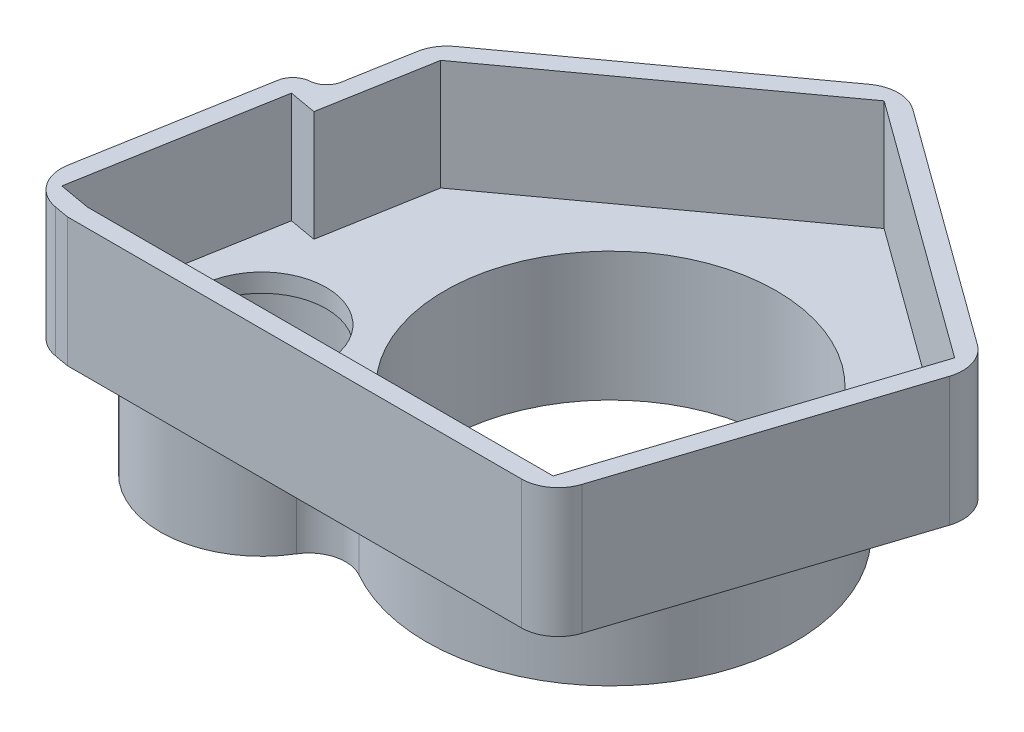
SolidWorks part; units mm, degrees
ref_plane "Front Plane" through (0, 0, 0) normal (0, 0, 1) x (1, 0, 0)
ref_plane "Top Plane" through (0, 0, 0) normal (0, 1, 0) x (1, 0, 0)
ref_plane "Right Plane" through (0, 0, 0) normal (1, 0, 0) x (0, 0, -1)
sketch "Sketch1" plane through (0, 0, 0) normal (0, 1, 0) x (1, 0, 0)
  line L0 (0, -73) -> (68.7664, -23.0383) construction
  line L1 (-68.7664, -23.0383) -> (0, -73) construction
  line L2 (68.7664, -23.0383) -> (42.5, 57.8016) construction
  line L3 (42.5, 57.8016) -> (-83.0207, 57.8016) construction
  line L4 (-83.0207, 57.8016) -> (-90.4067, 56.4992) construction
  line L5 (-90.4067, 56.4992) -> (-81.4141, 5.4992) construction
  line L6 (-81.4141, 5.4992) -> (-74.028, 6.8016) construction
  line L7 (-74.028, 6.8016) -> (-68.7664, -23.0383) construction
  line L8 (46.8593, 63.8016) -> (-83.5456, 63.8016)
  line L9 (-83.5456, 63.8016) -> (-97.3575, 61.3661) construction
  line L10 (-97.3575, 61.3661) -> (-86.281, -1.4515) construction
  line L11 (-86.281, -1.4515) -> (-78.895, -0.1492) construction
  line L12 (-78.895, -0.1492) -> (-74.2543, -26.4675) construction
  line L13 (-74.2543, -26.4675) -> (0, -80.4164) construction
  line L14 (0, -80.4164) -> (75.8199, -25.33) construction
  line L15 (75.8199, -25.33) -> (46.8593, 63.8016) construction
  line L16 (-74.028, 120.8016) -> (-68.7664, 150.6414) construction
  line L17 (-81.4141, 122.1039) -> (-74.028, 120.8016) construction
  line L18 (-90.4067, 71.1039) -> (-81.4141, 122.1039) construction
  line L19 (-83.0207, 69.8016) -> (-90.4067, 71.1039) construction
  line L20 (42.5, 69.8016) -> (-83.0207, 69.8016) construction
  line L21 (68.7664, 150.6414) -> (42.5, 69.8016) construction
  line L22 (-68.7664, 150.6414) -> (0, 200.6031) construction
  line L23 (0, 200.6031) -> (68.7664, 150.6414) construction
  line L24 (75.8199, 152.9332) -> (46.8593, 63.8016)
  line L25 (0, 208.0195) -> (75.8199, 152.9332)
  line L26 (-74.2543, 154.0706) -> (0, 208.0195)
  line L27 (-78.895, 127.7523) -> (-74.2543, 154.0706)
  line L28 (-86.281, 129.0546) -> (-78.895, 127.7523)
  line L29 (-97.3575, 66.237) -> (-86.281, 129.0546)
  line L30 (-83.5456, 63.8016) -> (-97.3575, 66.237)
  circle A0 centre (0, 0) radius 45 construction
  circle A1 centre (0, 127.6031) radius 45
  point P10 (-74.028, 6.8016)
  point P12 (0, 0)
  point P13 (-68.7664, -23.0383)
  point P14 (-68.7664, -23.0383)
  dimension "D16" = 90
  dimension "D1" = 85
  dimension "D2" = 85
  dimension "D3" = 125.5207
  dimension "D4" = 7.5
  dimension "D5" = 51
  dimension "D6" = 30.3001
  dimension "D7" = 85
  dimension "D8" = 57.8016
  dimension "D9" = 7.5
  dimension "D10" = 73
  dimension "D11" = 0
  dimension "D12" = 58.2816
  dimension "D13" = 90.4067
  dimension "D14" = 79.2223
  dimension "D15" = 74.028
  dimension "D17" = 72.523
  dimension "D18" = 137.5329
  dimension "D19" = 6
extrude "Boss-Extrude1" add sketch "Sketch1" along normal blind 35
sketch "Sketch2" plane through (0, 35, 0) normal (0, 1, 0) x (1, 0, 0)
  line L40 (69.942, 151.0233) -> (0, 201.8392)
  line L41 (43.2265, 68.8016) -> (69.942, 151.0233)
  line L42 (0, 201.8392) -> (-69.6811, 151.2129)
  line L43 (-69.6811, 151.2129) -> (-74.8392, 121.96)
  line L44 (-74.8392, 121.96) -> (-82.2252, 123.2624)
  line L45 (-82.2252, 123.2624) -> (-91.5652, 70.2928)
  line L46 (-91.5652, 70.2928) -> (-83.1082, 68.8016)
  line L47 (-83.1082, 68.8016) -> (43.2265, 68.8016)
  line L48 (69.942, 151.0233) -> (0, 201.8392)
  line L49 (43.2265, 68.8016) -> (69.942, 151.0233)
  line L50 (0, 201.8392) -> (-69.6811, 151.2129)
  line L51 (-69.6811, 151.2129) -> (-74.8392, 121.96)
  line L52 (-74.8392, 121.96) -> (-82.2252, 123.2624)
  line L53 (-82.2252, 123.2624) -> (-91.5652, 70.2928)
  line L54 (-91.5652, 70.2928) -> (-83.1082, 68.8016)
  line L55 (-83.1082, 68.8016) -> (43.2265, 68.8016)
  dimension "D1" = 1
extrude "Cut-Extrude1" cut sketch "Sketch2" against normal blind 30
sketch "Sketch4" plane through (0, 0, 0) normal (0, -1, 0) x (1, 0, 0)
  line L0 (-97.3575, -66.237) -> (-86.281, -129.0546) construction
  circle A0 centre (-61.8532, -94.8284) radius 22.5
  circle A1 centre (0, -127.6031) radius 45 construction
  circle A2 centre (0, -127.6031) radius 45
  arc A4 (-38.2941, -80.6433) -> (-60.3607, -122.2879) centre (-61.8532, -94.8284) ccw
  circle A5 centre (0, -127.6031) radius 50
  arc A6 (-49.8483, -131.4948) -> (-24.7727, -84.1714) centre (0, -127.6031) ccw
  arc A7 (-24.7727, -84.1714) -> (-38.2941, -80.6433) centre (-29.7272, -75.485) cw
  circle A8 centre (-61.8532, -94.8284) radius 27.5 construction
  circle A9 centre (-61.8532, -94.8284) radius 22.5 construction
  arc A10 (-49.8483, -131.4948) -> (-60.3607, -122.2879) centre (-59.818, -132.2732) ccw
  point P4 (-40.3364, -88.2501)
  point P10 (-34.3532, -94.8284)
  point P15 (0, 0)
  point P17 (-43.0049, -114.3523)
  point P19 (-46.9658, -111.6989)
  dimension "D2" = 45
  dimension "D5" = 10
  dimension "D1" = 30
  dimension "D3" = 5
  dimension "80" = 70
  dimension "D4" = 5
extrude "Boss-Extrude6" add sketch "Sketch4" along normal blind 30
sketch "Sketch11" plane through (0, 0, 0) normal (0, -1, 0) x (1, 0, 0)
  circle A3 centre (-61.8532, -94.8284) radius 17.5
  circle A4 centre (-61.8532, -94.8284) radius 17.5
  dimension "D1" = 5
extrude "Cut-Extrude5" cut sketch "Sketch11" against normal through all both and the other way through all
fillet "Fillet5" radius 10 5 edges at (46.8593, 17.5, -63.8016) (-97.3575, 17.5, -66.237) (-74.2543, 17.5, -154.0706) (0, 17.5, -208.0195) (75.8199, 17.5, -152.9332)
fillet "Fillet7" radius 5 1 edges at (-78.895, 17.5, -127.7523)
fillet "Fillet8" radius 5 1 edges at (-86.281, 17.5, -129.0546)
